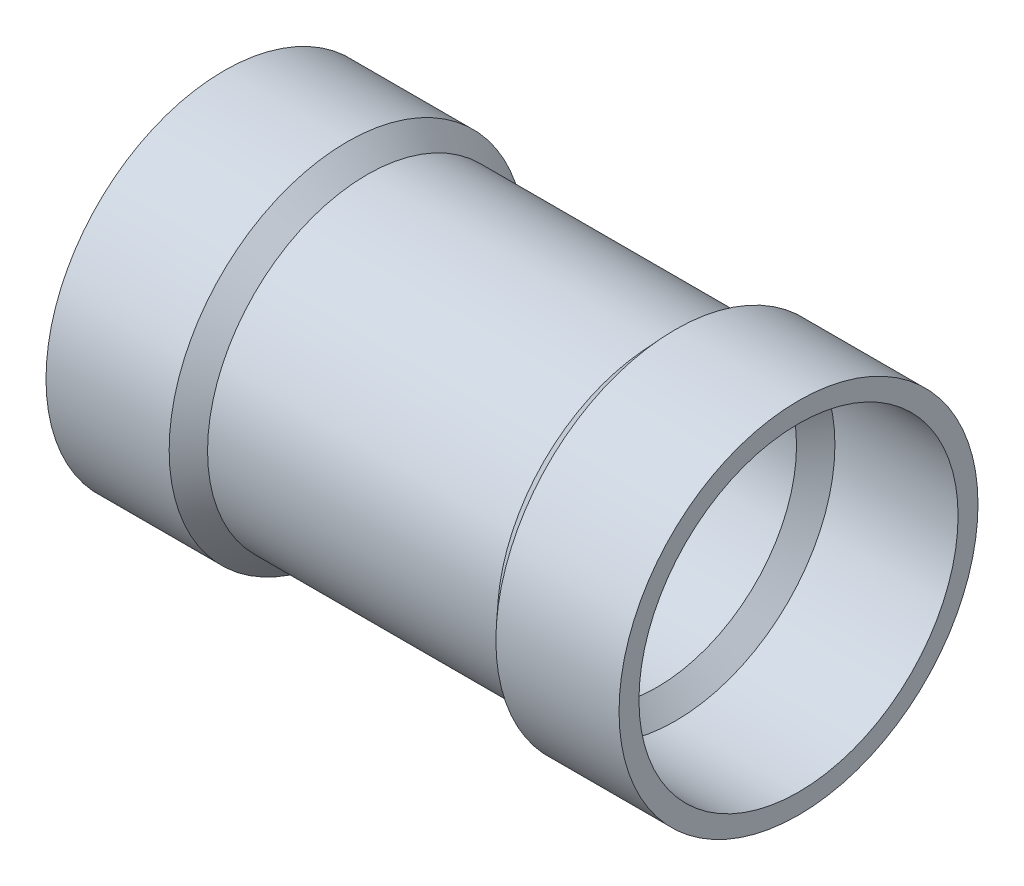
SolidWorks part; units mm, degrees
material "ABS"
ref_plane "Front Plane" through (0, 0, 0) normal (0, 0, 1) x (1, 0, 0)
ref_plane "Top Plane" through (0, 0, 0) normal (0, 1, 0) x (1, 0, 0)
ref_plane "Right Plane" through (0, 0, 0) normal (1, 0, 0) x (0, 0, -1)
sketch "Sketch3" plane through (0, 0, 0) normal (0, 0, 1) x (1, 0, 0)
  line L0 (-79.5, 0) -> (75.2413, 0) construction
  line L1 (-79.5, 0) -> (-79.5, 49.15) construction
  line L2 (-79.5, 49.15) -> (-45.5, 49.15)
  line L3 (-45.5, 49.15) -> (-40, 44.051)
  line L4 (-40, 44.051) -> (40, 44.051)
  line L5 (40, 44.051) -> (45.099, 49.551)
  line L6 (45.099, 49.551) -> (79.099, 49.551)
  line L7 (79.099, 49.551) -> (79.099, 44.051)
  line L8 (79.099, 44.051) -> (45.099, 44.051)
  line L9 (45.099, 44.051) -> (40, 38.551)
  line L10 (40, 38.551) -> (-40, 38.551)
  line L11 (-40, 38.551) -> (-45.5, 43.65)
  line L12 (-45.5, 43.65) -> (-79.5, 43.65)
  line L13 (-79.5, 43.65) -> (-79.5, 49.15)
  line L14 (0, 38.551) -> (0, 0) construction
  dimension "D1" = 49.15
  dimension "D2" = 34
  dimension "D3" = 80
  dimension "D4" = 7.5
  dimension "D5" = 5.5
revolve "Revolve1" add sketch "Sketch3" angle 360 about L0
sketch "Sketch4" plane through (79.099, 0, 0) normal (1, 0, 0) x (0, 0, -1)
